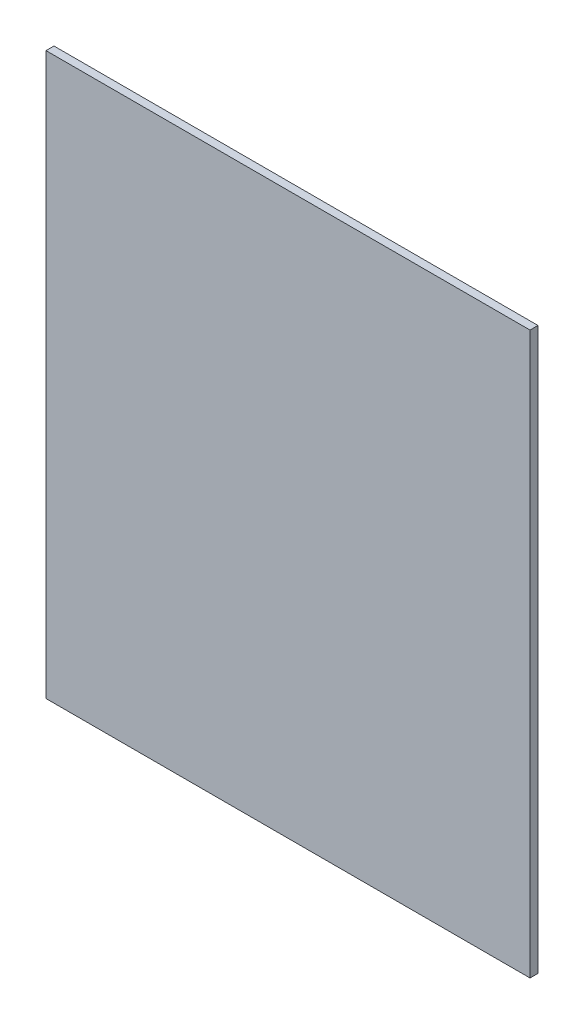
SolidWorks part; units mm, degrees
ref_plane "前视基准面" through (0, 0, 0) normal (0, 0, 1) x (1, 0, 0)
ref_plane "上视基准面" through (0, 0, 0) normal (0, 1, 0) x (1, 0, 0)
ref_plane "右视基准面" through (0, 0, 0) normal (1, 0, 0) x (0, 0, -1)
other "Configuration Table"
sketch "草图1" plane through (0, 0, 0) normal (0, 0, 1) x (1, 0, 0)
  line L0 (0, 0) -> (182, 0)
  line L1 (182, 0) -> (182, 211)
  line L2 (182, 211) -> (0, 211)
  line L3 (0, 211) -> (0, 0)
  dimension "width" = 182
  dimension "height" = 211
extrude "BlockExtrude" add sketch "草图1" along normal blind 3
